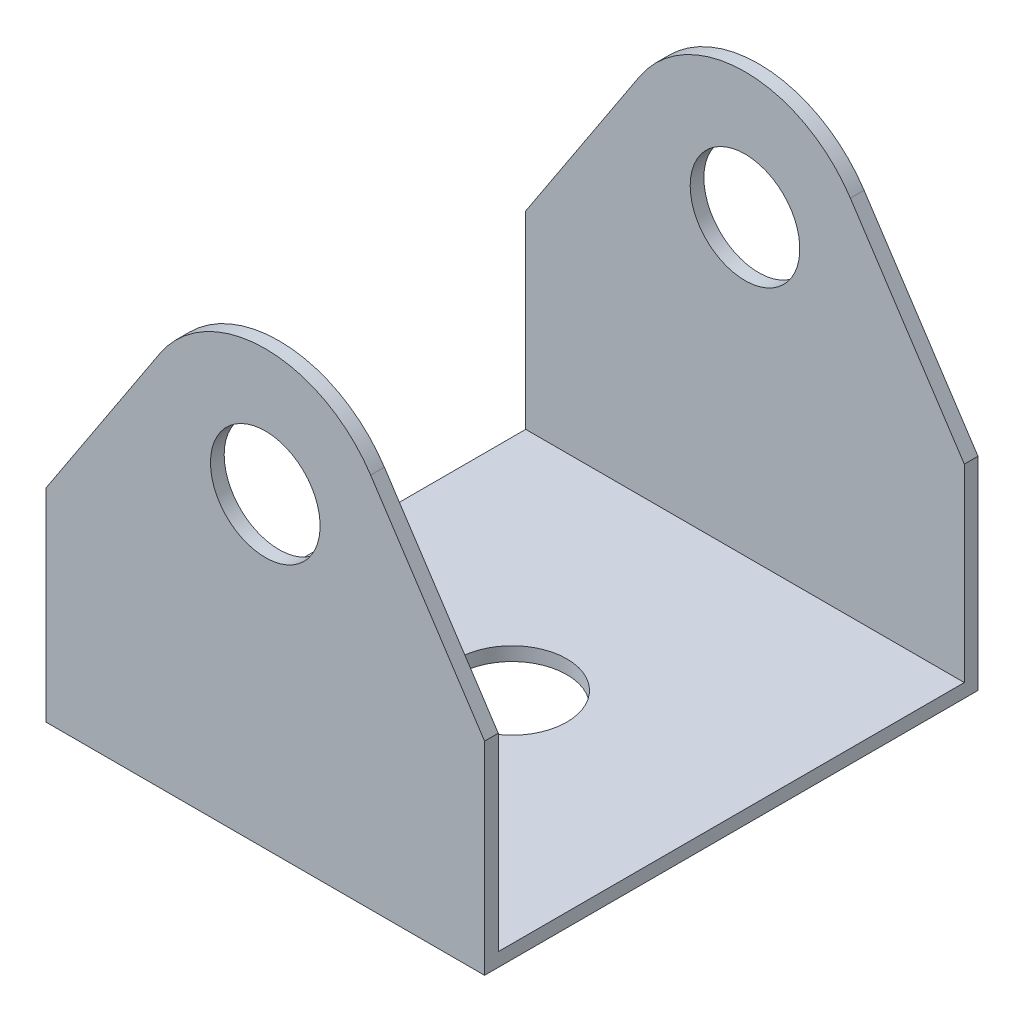
SolidWorks part; units mm, degrees
ref_plane "Plan de face" through (0, 0, 0) normal (0, 0, 1) x (1, 0, 0)
ref_plane "Plan de dessus" through (0, 0, 0) normal (0, 1, 0) x (1, 0, 0)
ref_plane "Plan de droite" through (0, 0, 0) normal (1, 0, 0) x (0, 0, -1)
sketch "Esquisse1" plane through (0, 0, 0) normal (0, 0, 1) x (1, 0, 0)
  line L0 (40, -56) -> (-40, -56)
  line L1 (-40, -19) -> (-40, -56)
  line L2 (0, 0) -> (0, -98.0836) construction
  line L3 (-40, -19) -> (-19.2233, 12.628)
  line L4 (0, 0) -> (0, 94.6013) construction
  line L5 (45.5595, 58.6907) -> (45.2694, 58.6907) construction
  line L6 (40, -19) -> (40, -56)
  line L7 (40, -19) -> (19.2233, 12.628)
  arc A0 (19.2233, 12.628) -> (-19.2233, 12.628) centre (0, 0) ccw
  point P11 (0, -56)
  dimension "D2" = 46
  dimension "D4" = 37
  dimension "D1" = 56
  dimension "D3" = 40
extrude "Extrusion1" add sketch "Esquisse1" along normal blind 90
shell "Coque1" thickness 2.5
sketch "Esquisse2" plane through (0, -56, 0) normal (0, -1, 0) x (1, 0, 0)
  line L0 (-40, 90) -> (-40, 0) construction
  line L1 (-40, 0) -> (40, 0) construction
  circle A0 centre (0, 45) radius 10
  dimension "D1" = 20
  dimension "D2" = 40
  dimension "D3" = 45
extrude "Enlèv. mat.-Extru.1" cut sketch "Esquisse2" against normal blind 90
sketch "Esquisse3" plane through (0, 0, 0) normal (0, 0, -1) x (-1, 0, 0)
  circle A0 centre (0, 0) radius 10
  arc A1 (19.2233, 12.628) -> (-19.2233, 12.628) centre (0, 0) ccw construction
  dimension "D1" = 20
extrude "Enlèv. mat.-Extru.2" cut sketch "Esquisse3" against normal through all
